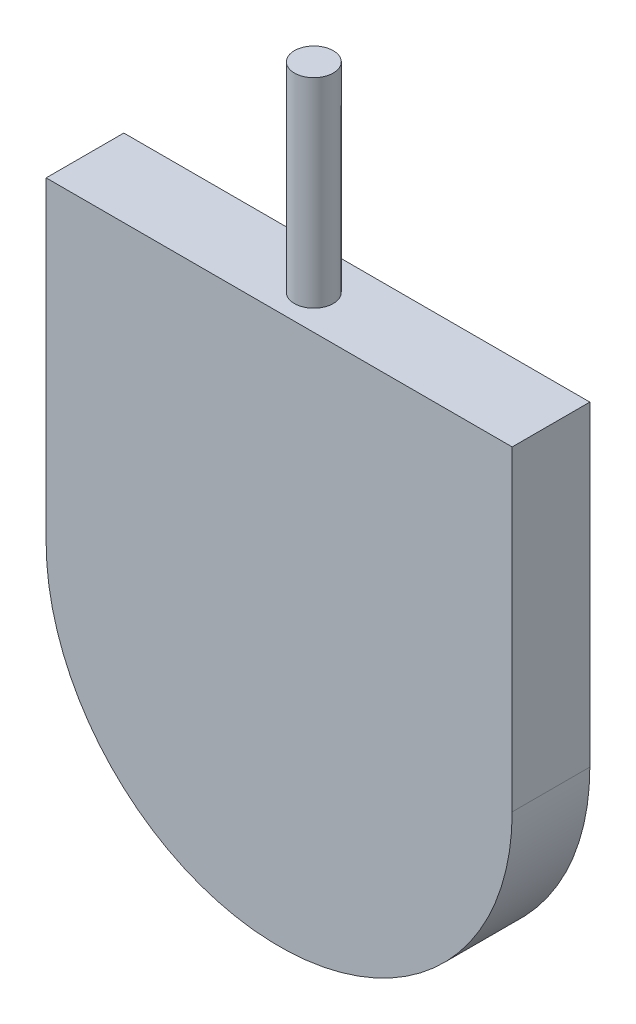
SolidWorks part; units mm, degrees
ref_plane "Front Plane" through (0, 0, 0) normal (0, 0, 1) x (1, 0, 0)
ref_plane "Top Plane" through (0, 0, 0) normal (0, 1, 0) x (1, 0, 0)
ref_plane "Right Plane" through (0, 0, 0) normal (1, 0, 0) x (0, 0, -1)
sketch "Sketch1" plane through (0, 0, 0) normal (0, 0, 1) x (1, 0, 0)
  line L0 (-38.1, 0) -> (-38.1, 51.6824)
  line L1 (-38.1, 51.6824) -> (38.1, 51.6824)
  line L2 (38.1, 51.6824) -> (38.1, 0)
  arc A0 (-38.1, 0) -> (38.1, 0) centre (0, 0) ccw
  dimension "D1" = 76.2
extrude "Boss-Extrude1" add sketch "Sketch1" along normal blind 12.7
sketch "Sketch2" plane through (0, 0, 0) normal (0, 1, 0) x (1, 0, 0)
  circle A0 centre (0, -7.032) radius 3.175
  dimension "D1" = 6.35
extrude "Boss-Extrude2" add sketch "Sketch2" along normal blind 84.328
